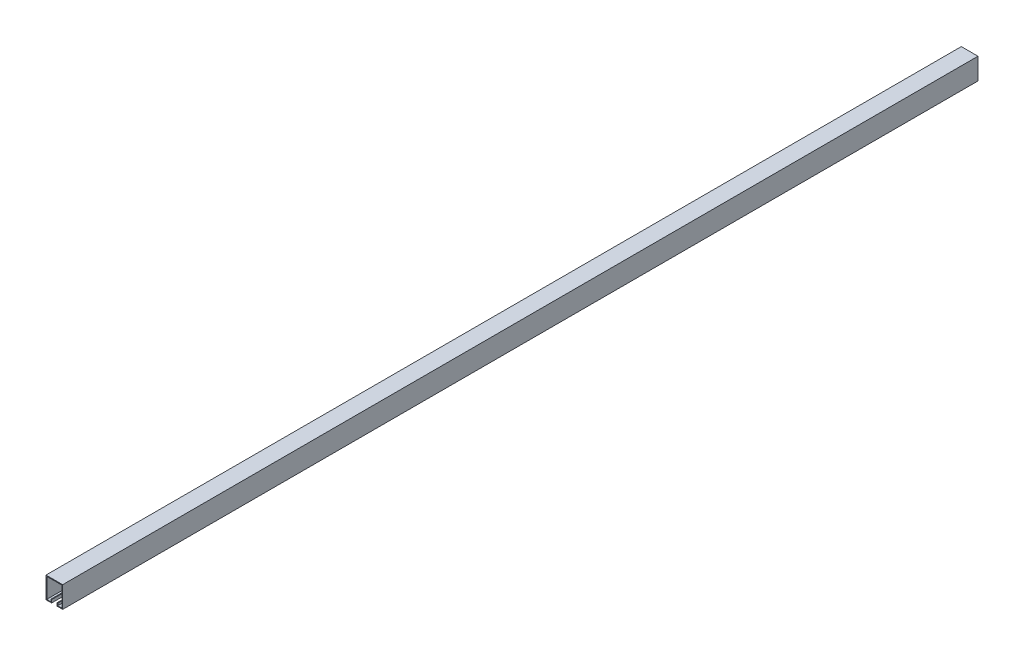
SolidWorks part; units mm, degrees
ref_plane "Alzado" through (0, 0, 0) normal (0, 0, 1) x (1, 0, 0)
ref_plane "Planta" through (0, 0, 0) normal (0, 1, 0) x (1, 0, 0)
ref_plane "Vista lateral" through (0, 0, 0) normal (1, 0, 0) x (0, 0, -1)
sketch "Croquis1" plane through (0, 0, 0) normal (0, 0, 1) x (1, 0, 0)
  line L1 (0, 0) -> (44.45, 0)
  line L2 (0, 0) -> (0, -57.15)
  line L3 (0, -57.15) -> (44.45, -57.15)
  line L4 (44.45, 0) -> (44.45, -57.15)
  point P5 (44.45, -28.575)
  dimension "D1" = 44.45
  dimension "D2" = 57.15
extrude "Saliente-Extruir1" add sketch "Croquis1" along normal blind 2440
sketch "Croquis2" plane through (0, 0, 2440) normal (0, 0, 1) x (1, 0, 0)
  line L0 (15, -57.15) -> (15, -49.15)
  line L1 (0, -57.15) -> (44.45, -57.15) construction
  line L2 (15, -49.15) -> (13, -49.15)
  line L3 (13, -49.15) -> (13, -55.15)
  line L4 (13, -55.15) -> (2, -55.15)
  line L5 (2, -55.15) -> (2, -2)
  line L6 (2, -2) -> (42.45, -2)
  line L7 (42.45, -2) -> (42.45, -55.15)
  line L8 (42.45, -55.15) -> (31.45, -55.15)
  line L9 (31.45, -55.15) -> (31.45, -49.15)
  line L10 (31.45, -49.15) -> (29.45, -49.15)
  line L11 (29.45, -49.15) -> (29.45, -57.15)
  line L12 (29.45, -57.15) -> (15, -57.15)
  line L13 (44.45, 0) -> (0, 0) construction
  line L14 (44.45, -57.15) -> (44.45, 0) construction
  line L15 (0, 0) -> (0, -57.15) construction
  dimension "D1" = 2
  dimension "D2" = 2
  dimension "D3" = 2
  dimension "D4" = 2
  dimension "D5" = 2
  dimension "D6" = 11
  dimension "D7" = 11
  dimension "D8" = 6
  dimension "D9" = 6
  dimension "D10" = 2
  dimension "D11" = 2
  dimension "D12" = 14.45
extrude "Cortar-Extruir1" cut sketch "Croquis2" against normal up to surface (2440 mm away) up to face at (22.225, -28.575, 0)
